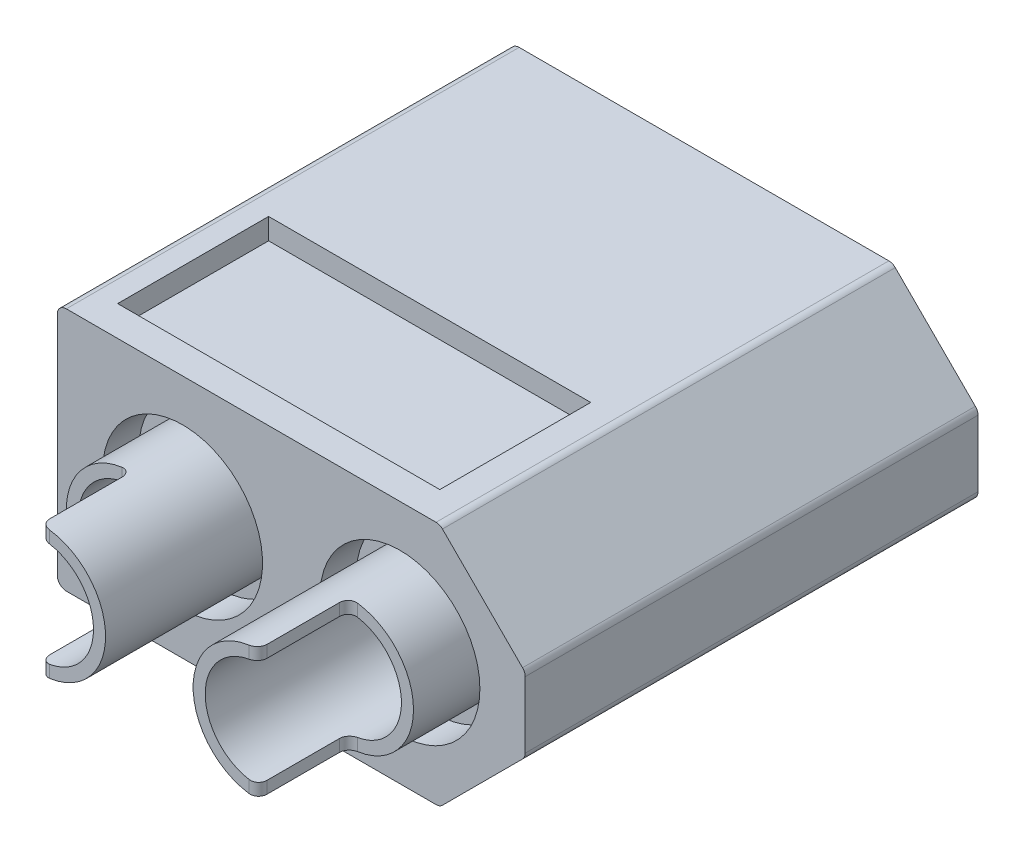
SolidWorks part; units mm, degrees
ref_plane "Спереди" through (0, 0, 0) normal (0, 0, 1) x (1, 0, 0)
ref_plane "Сверху" through (0, 0, 0) normal (0, 1, 0) x (1, 0, 0)
ref_plane "Справа" through (0, 0, 0) normal (1, 0, 0) x (0, 0, -1)
sketch "Эскиз1" plane through (0, 0, 0) normal (0, 0, 1) x (1, 0, 0)
  line L0 (4.9216, 4.05) -> (7.75, 1.2216)
  line L1 (-7.75, 4.05) -> (7.75, 4.05)
  line L2 (-7.75, 4.05) -> (-7.75, -4.05)
  line L3 (-7.75, -4.05) -> (7.75, -4.05)
  line L4 (7.75, 4.05) -> (7.75, -4.05)
  line L5 (-7.75, 4.05) -> (7.75, -4.05) construction
  line L6 (-7.75, -4.05) -> (7.75, 4.05) construction
  line L7 (0, 0) -> (7.75, 0) construction
  line L8 (4.9216, -4.05) -> (7.75, -1.2216)
  point P0 (0, 0)
  dimension "D1" = 8.1
  dimension "D2" = 15.5
  dimension "D3" = 45
  dimension "D4" = 4
extrude "Бобышка-Вытянуть1" add sketch "Эскиз1" along normal blind 15 contours L3 L8 L4 L0 L1 L2
sketch "Эскиз2" plane through (0, 0, 0) normal (0, 0, -1) x (-1, 0, 0)
  line L12 (-4.6316, -3.35) -> (7.05, -3.35)
  line L13 (7.05, -3.35) -> (7.05, 3.35)
  line L14 (7.05, 3.35) -> (-4.6316, 3.35)
  line L15 (-4.6316, 3.35) -> (-7.05, 0.9316)
  line L16 (-7.05, 0.9316) -> (-7.05, -0.9316)
  line L17 (-7.05, -0.9316) -> (-4.6316, -3.35)
  line L18 (-4.6316, -3.35) -> (7.05, -3.35)
  line L19 (7.05, -3.35) -> (7.05, 3.35)
  line L20 (7.05, 3.35) -> (-4.6316, 3.35)
  line L21 (-4.6316, 3.35) -> (-7.05, 0.9316)
  line L22 (-7.05, 0.9316) -> (-7.05, -0.9316)
  line L23 (-7.05, -0.9316) -> (-4.6316, -3.35)
  dimension "D1" = 0.7
extrude "Вырез-Вытянуть1" cut sketch "Эскиз2" against normal blind 7.7
ref_plane "Плоскость1" through (0, 0, 1.5) normal (0, 0, -1) x (-1, 0, 0)
sketch "Эскиз3" plane through (0, 0, 1.5) normal (0, 0, -1) x (-1, 0, 0)
  line L1 (7.05, 3.35) -> (-4.6316, 3.35) construction
  line L2 (-0.75, 2.15) -> (0.75, 2.15)
  line L3 (-0.75, 2.15) -> (-0.75, 3.35)
  line L4 (-0.75, 3.35) -> (0.75, 3.35)
  line L5 (0.75, 2.15) -> (0.75, 3.35)
  line L6 (-0.75, 2.15) -> (0.75, 3.35) construction
  line L7 (-0.75, 3.35) -> (0.75, 2.15) construction
  point P1 (0, 2.75)
  dimension "D1" = 1.2
  dimension "D2" = 1.5
extrude "Бобышка-Вытянуть2" add sketch "Эскиз3" against normal up to surface (6.2 mm away) up to face at (1.5439, 0, 7.7)
sketch "Эскиз4" plane through (0, 0, 7.7) normal (0, 0, -1) x (-1, 0, 0)
  line L1 (0.75, 2.15) -> (-0.75, 2.15)
  line L2 (0.75, 2.15) -> (0.75, -1.85)
  line L3 (0.75, -1.85) -> (-0.75, -1.85)
  line L4 (-0.75, 2.15) -> (-0.75, -1.85)
  dimension "D1" = 4
  dimension "D2" = 1.5
extrude "Вырез-Вытянуть2" cut sketch "Эскиз4" against normal blind 1.2
sketch "Эскиз5" plane through (0, 0, 7.7) normal (0, 0, -1) x (-1, 0, 0)
  line L0 (0, 0) -> (0, -2.5029) construction
  circle A0 centre (3.6, 0) radius 2.15
  circle A1 centre (-3.6, 0) radius 2.15
  dimension "D1" = 4.3
  dimension "D2" = 7.2
extrude "Бобышка-Вытянуть3" add sketch "Эскиз5" along normal offset from surface 1.2 and the other way offset from surface (12 mm away) 4.7 up to face at (1.5439, 0, 0) other way up to face at (1.6405, 0, 15)
sketch "Эскиз6" plane through (0, 0, 15) normal (0, 0, 1) x (1, 0, 0)
  line L0 (0, 0) -> (0, -1.6207) construction
  circle A0 centre (3.6, 0) radius 2.15
  circle A1 centre (3.6, 0) radius 2.65
  circle A3 centre (3.6, 0) radius 2.15 construction
  circle A4 centre (-3.6, 0) radius 2.65
  circle A5 centre (-3.6, 0) radius 2.15
  dimension "D1" = 0.5
extrude "Вырез-Вытянуть3" cut sketch "Эскиз6" against normal blind 1.2
sketch "Эскиз7" plane through (0, 0, 19.7) normal (0, 0, 1) x (1, 0, 0)
  line L0 (0, 0) -> (0, 2.5309) construction
  circle A0 centre (-3.6, 0) radius 1.75
  circle A1 centre (-3.6, 0) radius 2.15 construction
  circle A2 centre (3.6, 0) radius 1.75
  dimension "D1" = 0.4
extrude "Вырез-Вытянуть4" cut sketch "Эскиз7" against normal blind 9
sketch "Эскиз8" plane through (0, 0, 0) normal (0, 1, 0) x (1, 0, 0)
  line L0 (0, 0) -> (0, -21.1053) construction
  line L1 (3.6, -19.7) -> (3.6, -16.7)
  line L2 (-5.75, -19.7) -> (-3.6, -19.7)
  line L3 (-5.75, -19.7) -> (-5.75, -16.7)
  line L4 (-5.75, -16.7) -> (-3.6, -16.7)
  line L5 (-3.6, -19.7) -> (-3.6, -16.7)
  line L6 (5.75, -16.7) -> (3.6, -16.7)
  line L7 (5.75, -19.7) -> (5.75, -16.7)
  line L8 (5.75, -19.7) -> (3.6, -19.7)
  dimension "D1" = 3
  dimension "D2" = 2.15
extrude "Вырез-Вытянуть5" cut sketch "Эскиз8" against normal through all both and the other way through all
sketch "Эскиз10" plane through (0, 0, 1.2) normal (0, 0, -1) x (-1, 0, 0)
  line L0 (0, 0) -> (0, -1.477) construction
  circle A0 centre (3.6, 0) radius 1.95
  circle A2 centre (3.6, 0) radius 2.15 construction
  circle A3 centre (3.6, 0) radius 2.15
  circle A5 centre (3.6, 0) radius 2.15 construction
  circle A6 centre (-3.6, 0) radius 2.15
  circle A7 centre (-3.6, 0) radius 1.95
  dimension "D1" = 0.2
extrude "Вырез-Вытянуть7" cut sketch "Эскиз10" against normal offset from surface (5.5 mm away) 1 up to face at (5.75, 0, 7.7)
sketch "Эскиз9" plane through (0, 0, 1.2) normal (0, 0, -1) x (-1, 0, 0)
  line L0 (0, 0) -> (0, -2.4191) construction
  line L1 (3.6, 2.5) -> (3.6, -2.5) construction
  line L2 (3.75, -2.5) -> (3.45, -2.5)
  line L3 (3.75, -2.5) -> (3.75, -0.7348)
  line L4 (3.75, 2.5) -> (3.45, 2.5)
  line L5 (3.45, -2.5) -> (3.45, -0.7348)
  line L6 (6.1, 0) -> (1.1, 0) construction
  line L7 (-3.75, -2.5) -> (-3.45, -2.5)
  line L8 (6.1, -0.15) -> (4.3348, -0.15)
  line L9 (6.1, -0.15) -> (6.1, 0.15)
  line L10 (6.1, 0.15) -> (4.3348, 0.15)
  line L11 (1.1, -0.15) -> (1.1, 0.15)
  line L12 (-3.45, -2.5) -> (-3.45, -0.7348)
  line L13 (-2.8652, -0.15) -> (-1.1, -0.15)
  line L14 (-1.1, -0.15) -> (-1.1, 0.15)
  line L15 (-2.8652, 0.15) -> (-1.1, 0.15)
  line L16 (-3.45, 0.7348) -> (-3.45, 2.5)
  line L17 (3.75, -0.009) -> (3.75, 0.009)
  line L18 (-3.75, 2.5) -> (-3.45, 2.5)
  line L19 (-3.75, 0.7348) -> (-3.75, 2.5)
  line L20 (-6.1, 0.15) -> (-4.3348, 0.15)
  line L21 (2.8652, -0.15) -> (1.1, -0.15)
  line L22 (-6.1, -0.15) -> (-6.1, 0.15)
  line L23 (-6.1, -0.15) -> (-4.3348, -0.15)
  line L24 (2.8652, 0.15) -> (1.1, 0.15)
  line L25 (3.45, 0.7348) -> (3.45, 2.5)
  line L26 (-3.75, -2.5) -> (-3.75, -0.7348)
  line L28 (3.75, 0.7348) -> (3.75, 2.5)
  arc A0 (3.45, 0.7348) -> (2.8652, 0.15) centre (3.6, 0) ccw
  arc A1 (2.8652, -0.15) -> (3.45, -0.7348) centre (3.6, 0) ccw
  arc A2 (3.75, -0.7348) -> (4.3348, -0.15) centre (3.6, 0) ccw
  arc A3 (4.3348, 0.15) -> (3.75, 0.7348) centre (3.6, 0) ccw
  arc A4 (-2.8652, -0.15) -> (-3.45, -0.7348) centre (-3.6, 0) cw
  arc A5 (-3.45, 0.7348) -> (-2.8652, 0.15) centre (-3.6, 0) cw
  arc A6 (-4.3348, 0.15) -> (-3.75, 0.7348) centre (-3.6, 0) cw
  arc A7 (-3.75, -0.7348) -> (-4.3348, -0.15) centre (-3.6, 0) cw
  dimension "D1" = 1.5
  dimension "D2" = 5
  dimension "D3" = 0.3
  dimension "D4" = 0.3
  dimension "D5" = 5
extrude "Вырез-Вытянуть6" cut sketch "Эскиз9" against normal offset from surface (6 mm away) 0.5
fillet "Скругление1" radius 1 8 edges at (4.9789, 1.3789, 1.2) (2.2211, 1.3789, 1.2) (4.9789, -1.3789, 1.2) (2.2211, -1.3789, 1.2) (-2.2211, -1.3789, 1.2) (-4.9789, -1.3789, 1.2) (-4.9789, 1.3789, 1.2) (-2.2211, 1.3789, 1.2)
fillet "Скругление2" radius 0.3 8 edges at (3.6, 1.95, 16.7) (3.6, -1.95, 16.7) (-3.6, -1.95, 16.7) (-3.6, 1.95, 16.7) (3.6, 1.95, 19.7) (3.6, -1.95, 19.7) (-3.6, -1.95, 19.7) (-3.6, 1.95, 19.7)
sketch "Эскиз11" plane through (0, 4.05, 0) normal (0, 1, 0) x (1, 0, 0)
  line L0 (-7.75, -15) -> (-7.75, 0) construction
  line L1 (-6.75, -14) -> (3.9216, -14)
  line L2 (-6.75, -14) -> (-6.75, -9)
  line L3 (-6.75, -9) -> (3.9216, -9)
  line L4 (3.9216, -14) -> (3.9216, -9)
  line L5 (-7.75, -15) -> (4.9216, -15) construction
  line L6 (4.9216, -15) -> (4.9216, 0) construction
  dimension "D1" = 1
  dimension "D2" = 1
  dimension "D3" = 1
  dimension "D4" = 5
extrude "Вырез-Вытянуть8" cut sketch "Эскиз11" against normal blind 0.7
mirror "Зеркальное отражение1" about plane through (0, 0, 0) normal (0, 1, 0) of "Вырез-Вытянуть8"
sketch "Эскиз12" plane through (0, -3.35, 0) normal (0, -1, 0) x (1, 0, 0)
  line L0 (2.4216, 12.5) -> (-5.4393, 12.5) construction
  line L1 (-6.75, 14) -> (3.9216, 14) construction
  line L2 (3.9216, 14) -> (3.9216, 9) construction
  text T0 "XT-60" font "Arial" height 2
  dimension "D1" = 1.5
  dimension "D2" = 1.5
extrude "Бобышка-Вытянуть4" add sketch "Эскиз12" along normal blind 0.2
fillet "Скругление3" radius 0.3 6 edges at (-7.75, 4.05, 7.5) (-7.75, -4.05, 7.5) (4.9216, 4.05, 7.5) (7.75, 1.2216, 7.5) (7.75, -1.2216, 7.5) (4.9216, -4.05, 7.5)
